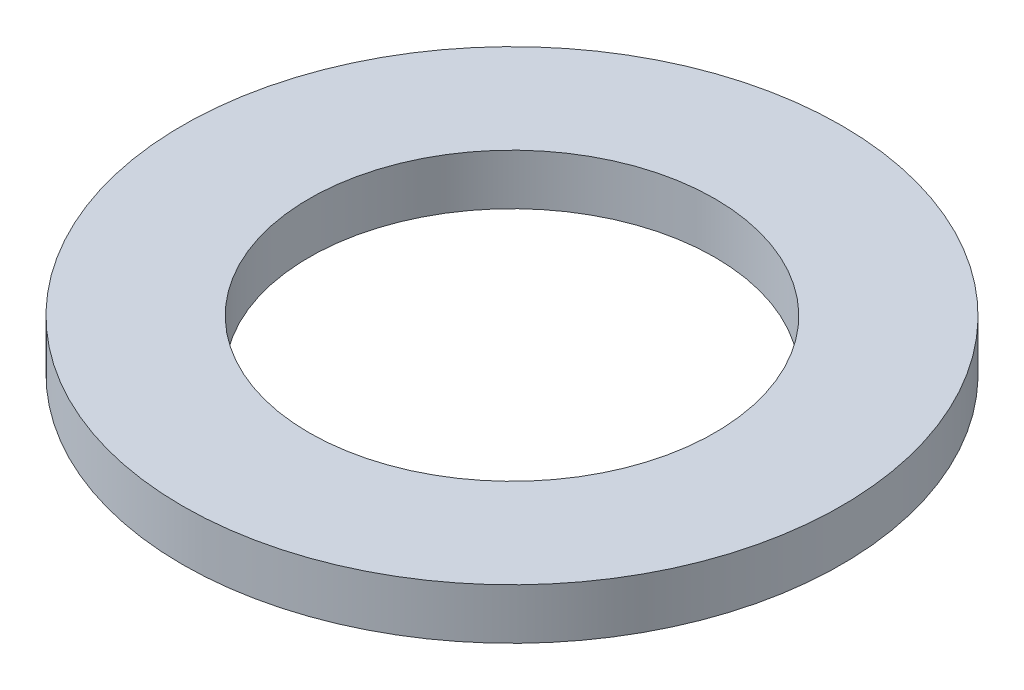
SolidWorks part; units mm, degrees
ref_plane "Front Plane" through (0, 0, 0) normal (0, 0, 1) x (1, 0, 0)
ref_plane "Top Plane" through (0, 0, 0) normal (0, 1, 0) x (1, 0, 0)
ref_plane "Right Plane" through (0, 0, 0) normal (1, 0, 0) x (0, 0, -1)
sketch "Sketch2" plane through (0, 0, 0) normal (0, 1, 0) x (1, 0, 0)
  circle A0 centre (0, 0) radius 13
  circle A1 centre (0, 0) radius 8
  dimension "D1" = 26
  dimension "D2" = 16
extrude "Boss-Extrude1" add sketch "Sketch2" along normal blind 2
